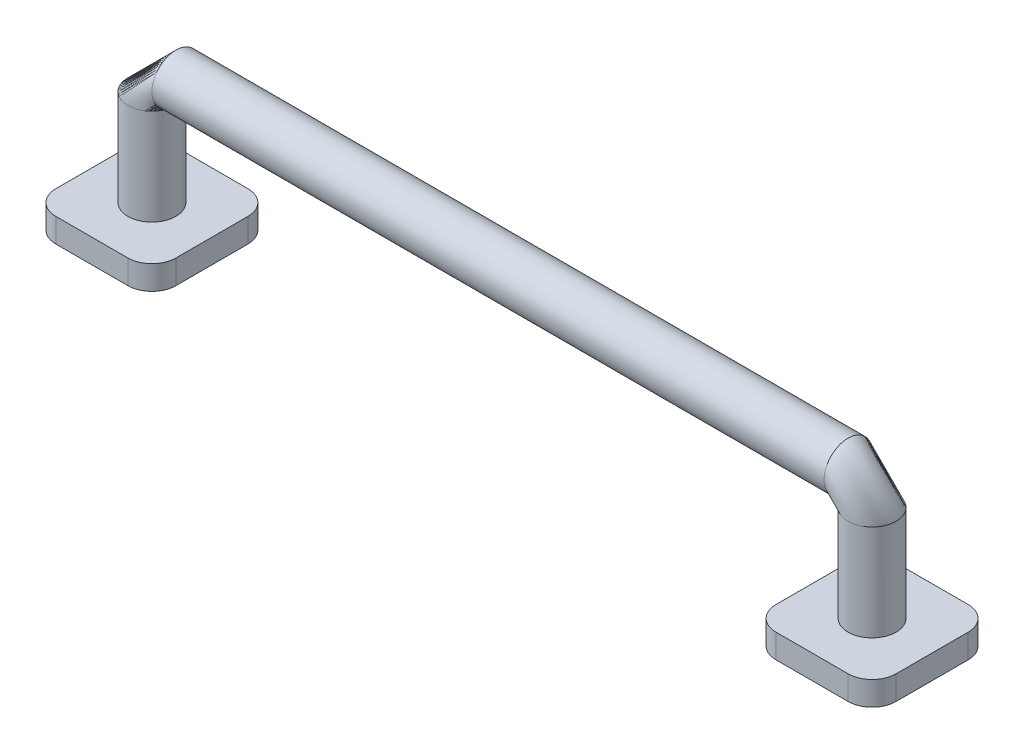
SolidWorks part; units mm, degrees
ref_plane "Front Plane" through (0, 0, 0) normal (0, 0, 1) x (1, 0, 0)
ref_plane "Top Plane" through (0, 0, 0) normal (0, 1, 0) x (1, 0, 0)
ref_plane "Right Plane" through (0, 0, 0) normal (1, 0, 0) x (0, 0, -1)
sketch "Sketch1" plane through (0, 0, 0) normal (0, 0, 1) x (1, 0, 0)
  line L1 (1535.3371, 0) -> (1535.3371, 400)
  line L2 (1435.3371, 500) -> (-1364.6629, 500)
  line L4 (-1464.6629, 400) -> (-1464.6629, 0)
  line L5 (-1464.6629, 0) -> (1535.3371, 0) construction
  arc A0 (1435.3371, 500) -> (1535.3371, 400) centre (1435.3371, 400) cw
  arc A1 (-1364.6629, 500) -> (-1464.6629, 400) centre (-1364.6629, 400) ccw
  point P3 (1535.3371, 500)
  point P9 (-1464.6629, 500)
  dimension "D3" = 100
  dimension "D1" = 3000
  dimension "D2" = 500
sweep "Sweep1" add path "Sketch1" circular profile diameter 200 parameters "D3"=200
sketch "Sketch79" plane through (0, 0, 0) normal (0, -1, 0) x (1, 0, 0)
  line L1 (-1614.6629, 250) -> (-1314.6629, 250)
  line L2 (-1714.6629, 150) -> (-1714.6629, -150)
  line L3 (-1614.6629, -250) -> (-1314.6629, -250)
  line L4 (-1214.6629, 150) -> (-1214.6629, -150)
  line L5 (-1714.6629, 250) -> (-1214.6629, -250) construction
  line L6 (-1714.6629, -250) -> (-1214.6629, 250) construction
  line L7 (1385.3371, 250) -> (1685.3371, 250)
  line L8 (1285.3371, 150) -> (1285.3371, -150)
  line L9 (1385.3371, -250) -> (1685.3371, -250)
  line L10 (1785.3371, 150) -> (1785.3371, -150)
  line L11 (1285.3371, 250) -> (1785.3371, -250) construction
  line L12 (1285.3371, -250) -> (1785.3371, 250) construction
  arc A0 (1785.3371, -150) -> (1685.3371, -250) centre (1685.3371, -150) cw
  arc A1 (1385.3371, -250) -> (1285.3371, -150) centre (1385.3371, -150) cw
  arc A2 (1685.3371, 250) -> (1785.3371, 150) centre (1685.3371, 150) cw
  arc A3 (1385.3371, 250) -> (1285.3371, 150) centre (1385.3371, 150) ccw
  arc A4 (-1314.6629, 250) -> (-1214.6629, 150) centre (-1314.6629, 150) cw
  arc A5 (-1314.6629, -250) -> (-1214.6629, -150) centre (-1314.6629, -150) ccw
  arc A6 (-1714.6629, -150) -> (-1614.6629, -250) centre (-1614.6629, -150) ccw
  arc A7 (-1614.6629, 250) -> (-1714.6629, 150) centre (-1614.6629, 150) ccw
  point P0 (-1464.6629, 0)
  point P6 (1535.3371, 0)
  point P12 (0, 0)
  point P13 (0, 0)
  dimension "D3" = 100
  dimension "D1" = 500
  dimension "D2" = 500
extrude "Boss-Extrude1" add sketch "Sketch79" along normal blind 100
